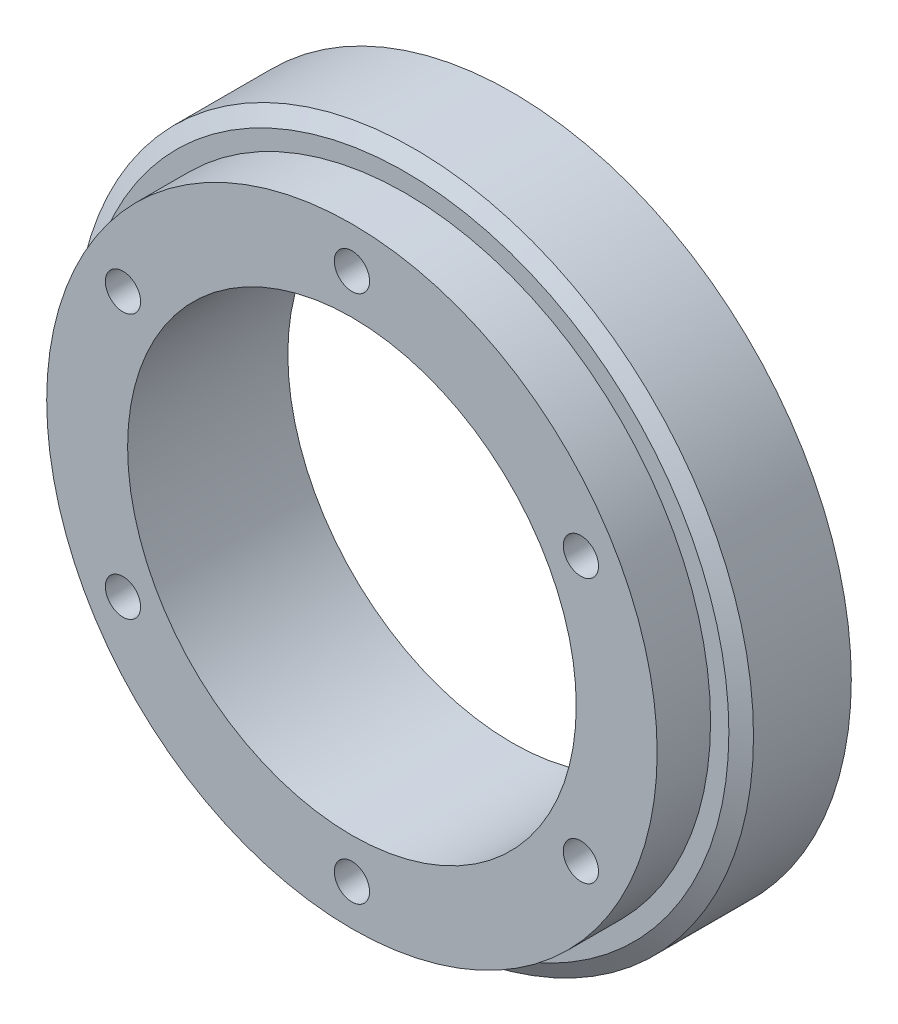
SolidWorks part; units mm, degrees
ref_plane "Front Plane" through (0, 0, 0) normal (0, 0, 1) x (1, 0, 0)
ref_plane "Top Plane" through (0, 0, 0) normal (0, 1, 0) x (1, 0, 0)
ref_plane "Right Plane" through (0, 0, 0) normal (1, 0, 0) x (0, 0, -1)
sketch "Sketch1" plane through (0, 0, 0) normal (1, 0, 0) x (0, 0, -1)
  line L0 (0, 31.75) -> (-9.1557, 31.75)
  line L1 (-9.1557, 31.75) -> (-10, 30.2876)
  line L4 (-15, 0) -> (0, 0) construction
  line L9 (-15, 28.575) -> (-15, 21)
  line L10 (-15, 21) -> (0, 21)
  line L11 (0, 21) -> (0, 31.75)
  line L12 (-15, -21) -> (0, -21) construction
  line L13 (-15, -28.575) -> (-15, -21) construction
  line L14 (-10, -30.2876) -> (-15, -28.575) construction
  line L15 (-9.1557, -31.75) -> (-10, -30.2876) construction
  line L16 (0, -31.75) -> (-9.1557, -31.75) construction
  line L17 (0, -21) -> (0, -31.75) construction
  line L18 (-15, 28.575) -> (-10, 28.575)
  line L19 (-10, 28.575) -> (-10, 30.2876)
  dimension "D1" = 63.5
  dimension "D2" = 3.175
  dimension "D3" = 30
  dimension "D4" = 42
  dimension "D5" = 10
  dimension "D6" = 15
  dimension "D7" = 1.4624
revolve "Revolve1" add sketch "Sketch1" angle 360 about L4
sketch "Sketch2" plane through (0, 0, 0) normal (0, 0, -1) x (-1, 0, 0)
  circle A0 centre (0, 0) radius 24.75 construction
  point P3 (0, 24.75)
  dimension "D1" = 49.5
hole_wizard "M4x0.7 Tapped Hole1" positions "Sketch2" profile "Sketch3" tap size "M4x0.7" standard "ANSI Metric" end condition through all
sketch "Sketch3" plane through (0, 24.75, 0) normal (1, 0, 0) x (0, 1, 0)
  line L0 (0, 0) -> (0, 15)
  line L1 (0, 15) -> (1.65, 15)
  line L2 (1.65, 15) -> (1.65, 0)
  line L5 (1.65, 0) -> (0, 0)
  line L11 (0, -6.35) -> (0, 107.95) construction
  dimension "Thru Tap Drill Dia." = 3.3
  dimension "Thru Tap Drill Depth" = 15
cosmetic thread "Hole Thread1" parameters "D2"=4
pattern_circular "CirPattern1" count 6 over 360 about axis through (0, 0, 0) along (0, 0, 1) of "M4x0.7 Tapped Hole1"
cosmetic thread "Hole Thread2"
cosmetic thread "Hole Thread3"
cosmetic thread "Hole Thread4"
cosmetic thread "Hole Thread5"
cosmetic thread "Hole Thread6"
